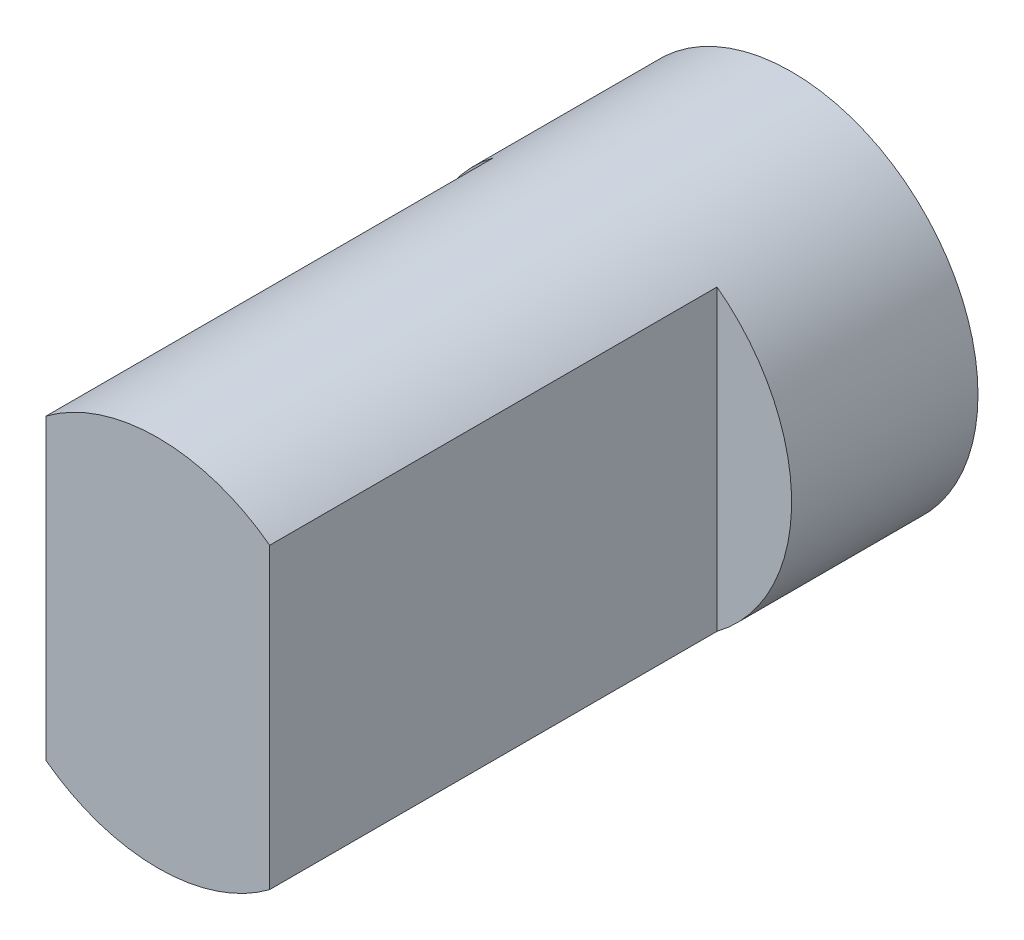
SolidWorks part; units mm, degrees
ref_plane "Front Plane" through (0, 0, 0) normal (0, 0, 1) x (1, 0, 0)
ref_plane "Top Plane" through (0, 0, 0) normal (0, 1, 0) x (1, 0, 0)
ref_plane "Right Plane" through (0, 0, 0) normal (1, 0, 0) x (0, 0, -1)
sketch "Sketch1" plane through (0, 0, 0) normal (0, 0, 1) x (1, 0, 0)
  circle A0 centre (0, 0) radius 2.5
  dimension "D1" = 5
extrude "Boss-Extrude1" add sketch "Sketch1" along normal blind 8.5
sketch "Sketch2" plane through (0, 0, 8.5) normal (0, 0, 1) x (1, 0, 0)
  line L0 (-1.5, 2) -> (-1.5, -2)
  line L1 (-1.5, 0) -> (1.5, 0) construction
  line L2 (1.5, 2) -> (1.5, -2)
  circle A0 centre (0, 0) radius 2.5 construction
  arc A1 (-1.5, 2) -> (-1.5, -2) centre (0, 0) ccw
  arc A2 (1.5, -2) -> (1.5, 2) centre (0, 0) ccw
  dimension "D1" = 3
extrude "Cut-Extrude1" cut sketch "Sketch2" against normal blind 6
